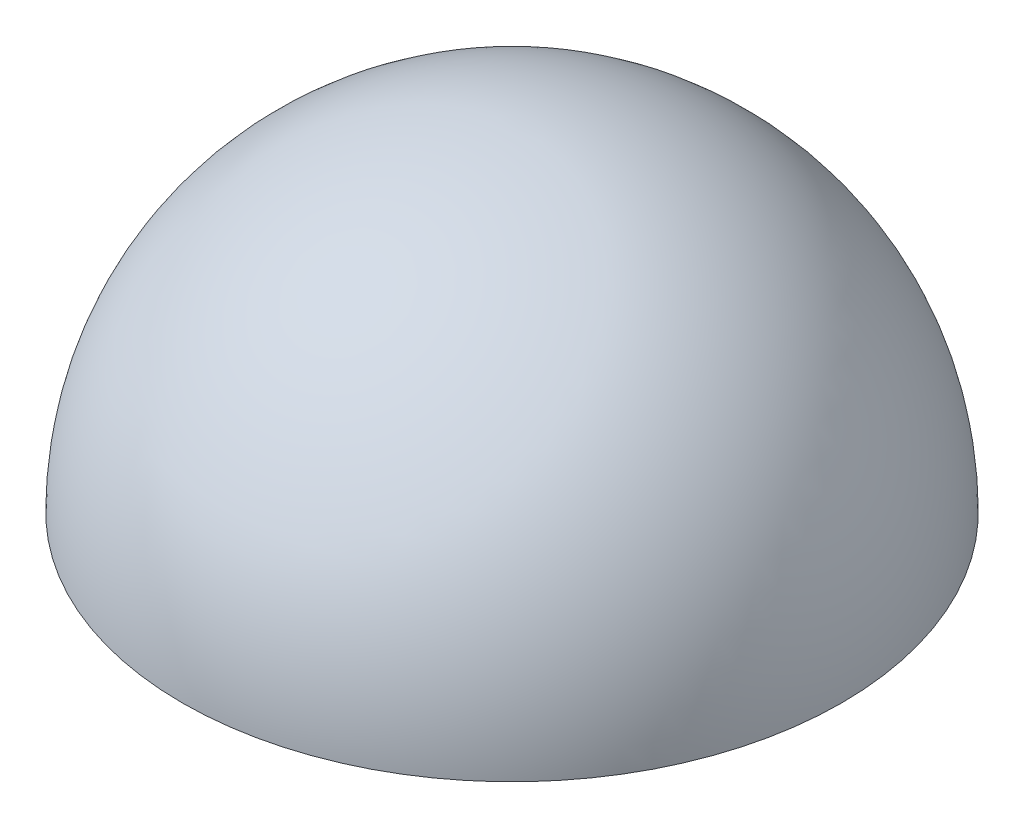
SolidWorks part; units mm, degrees
ref_plane "Front Plane" through (0, 0, 0) normal (0, 0, 1) x (1, 0, 0)
ref_plane "Top Plane" through (0, 0, 0) normal (0, 1, 0) x (1, 0, 0)
ref_plane "Right Plane" through (0, 0, 0) normal (1, 0, 0) x (0, 0, -1)
sketch "Sketch1" plane through (0, 0, 0) normal (0, 0, 1) x (1, 0, 0)
  line L0 (0, 0) -> (11.679, 0) construction
  line L1 (0, 0) -> (0, 10.1478) construction
  line L2 (0, 7.5) -> (0, 6.5)
  line L3 (6.5, 0) -> (7.5, 0)
  arc A0 (7.5, 0) -> (0, 7.5) centre (0, 0) ccw
  arc A1 (6.5, 0) -> (0, 6.5) centre (0, 0) ccw
  dimension "D1" = 13
  dimension "D2" = 15
revolve "Revolve1" add sketch "Sketch1" angle 360 about L1
